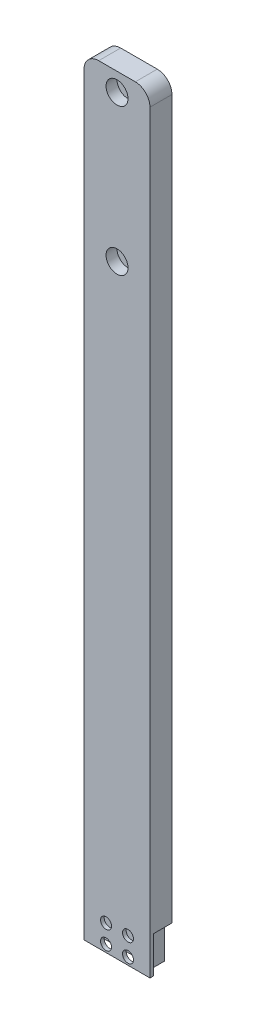
SolidWorks part; units mm, degrees
ref_plane "前视基准面" through (0, 0, 0) normal (0, 0, 1) x (1, 0, 0)
ref_plane "上视基准面" through (0, 0, 0) normal (0, 1, 0) x (1, 0, 0)
ref_plane "右视基准面" through (0, 0, 0) normal (1, 0, 0) x (0, 0, -1)
sketch "草图1" plane through (0, 0, 0) normal (0, 0, 1) x (1, 0, 0)
  line L0 (-33.0923, 146.8308) -> (-33.0923, -53.1692) construction
  line L1 (-42.0923, 146.8308) -> (-24.0923, 146.8308)
  line L2 (-42.0923, 146.8308) -> (-42.0923, -53.1692)
  line L3 (-42.0923, -53.1692) -> (-24.0923, -53.1692)
  line L4 (-24.0923, 146.8308) -> (-24.0923, -53.1692)
  circle A0 centre (-33.0923, 141.8308) radius 3
  circle A1 centre (-33.0923, 101.8308) radius 3
  dimension "D3" = 40
  dimension "D5" = 6
  dimension "D6" = 6
  dimension "D1" = 18
  dimension "D2" = 200
  dimension "D4" = 5
extrude "凸台-拉伸1" add sketch "草图1" along normal blind 6
sketch "草图2" plane through (0, -53.1692, 0) normal (0, -1, 0) x (1, 0, 0)
  line L0 (-33.0923, 0) -> (-33.0923, 6) construction
  line L6 (-40.0923, 5.4513) -> (-40.0923, 3)
  line L8 (-26.0923, 5.4513) -> (-26.0923, 3)
  line L9 (-40.0923, 5.4513) -> (-33.0923, 3) construction
  line L10 (-33.0923, 3) -> (-26.0923, 5.4513) construction
  line L11 (-24.0923, 0) -> (-42.0923, 0) construction
  line L12 (-24.0923, 6) -> (-42.0923, 6) construction
  line L13 (-42.0923, 3) -> (-33.0923, 3) construction
  line L14 (-42.0923, 6) -> (-42.0923, 0) construction
  line L15 (-24.0923, 6) -> (-24.0923, 0) construction
  line L19 (-26.0923, 5.4513) -> (-26.0923, 4.5513)
  line L21 (-40.0923, 5.4513) -> (-40.0923, 4.5513)
  line L22 (-26.0923, 5.4513) -> (-40.0923, 4.5513) construction
  line L23 (-26.0923, 4.5513) -> (-40.0923, 5.4513) construction
  line L24 (-24.0923, 0) -> (-42.0923, 0) construction
  line L25 (-26.0923, 3) -> (-40.0923, 3)
  line L27 (-26.0923, 4.5513) -> (-26.0923, 0)
  line L28 (-26.0923, 0) -> (-40.0923, 0)
  line L29 (-40.0923, 4.5513) -> (-40.0923, 0)
  line L30 (-26.0923, 4.5513) -> (-40.0923, 0) construction
  line L31 (-26.0923, 0) -> (-40.0923, 4.5513) construction
  point P4 (-33.0923, 3)
  point P18 (-33.0923, 3)
  point P19 (-33.0923, 3)
  point P23 (-33.0923, 5.0013)
  point P26 (-33.0923, 2.2757)
  line M2 (-42.0923, 0) -> (-24.0923, 0)
  dimension "D1" = 14
  dimension "D2" = 3
  dimension "D3" = 2
  dimension "D4" = 0.9
extrude "凸台-拉伸2" add sketch "草图2" along normal blind 10 contours L25 L29 L27 M2
sketch "草图3" plane through (0, 0, 6) normal (0, 0, 1) x (1, 0, 0)
  line L0 (-42.0923, -53.1692) -> (-24.0923, -53.1692) construction
  line L1 (-38.0923, -54.8692) -> (-35.5715, -54.8692) construction
  line L2 (-35.5715, -54.8692) -> (-33.0715, -54.8692) construction
  line L3 (-33.0715, -54.8692) -> (-30.0715, -54.8692) construction
  circle A0 centre (-38.0923, -54.8692) radius 1
  circle A1 centre (-35.5715, -54.8692) radius 1
  circle A2 centre (-33.0715, -54.8692) radius 1
  circle A3 centre (-30.0715, -54.8692) radius 1
  dimension "D1" = 1.7
sketch "草图4" plane through (0, 0, 6) normal (0, 0, 1) x (1, 0, 0)
  line L0 (-42.0923, -53.1692) -> (-24.0923, -53.1692) construction
  line L1 (-42.0923, -53.1692) -> (-24.0923, -53.1692)
  line L2 (-42.0923, -53.1692) -> (-42.0923, -57.1692)
  line L3 (-42.0923, -57.1692) -> (-24.0923, -57.1692)
  line L4 (-24.0923, -53.1692) -> (-24.0923, -57.1692)
  line L5 (-42.0923, -53.1692) -> (-24.0923, -57.1692) construction
  line L6 (-42.0923, -57.1692) -> (-24.0923, -53.1692) construction
  point P4 (-33.0923, -55.1692)
  dimension "D1" = 18
  dimension "D2" = 4
sketch "草图5" plane through (0, 0, 6) normal (0, 0, 1) x (1, 0, 0)
  line L1 (-42.0923, -53.1692) -> (-24.0923, -53.1692)
  line L2 (-42.0923, -53.1692) -> (-42.0923, -63.1692)
  line L3 (-42.0923, -63.1692) -> (-24.0923, -63.1692)
  line L4 (-24.0923, -53.1692) -> (-24.0923, -63.1692)
  line L5 (-42.0923, -53.1692) -> (-24.0923, -63.1692) construction
  line L6 (-42.0923, -63.1692) -> (-24.0923, -53.1692) construction
  point P4 (-33.0923, -58.1692)
  dimension "D1" = 18
  dimension "D2" = 10
extrude "凸台-拉伸4" add sketch "草图5" against normal blind 1
sketch "草图7" plane through (0, 0, 5) normal (0, 0, -1) x (-1, 0, 0)
  line L0 (40.0923, -63.1692) -> (40.0923, -53.1692) construction
  line L1 (42.0923, -63.1692) -> (24.0923, -63.1692) construction
  line L2 (24.0923, -53.1692) -> (26.0923, -53.1692) construction
  line L4 (40.0923, -53.1692) -> (42.0923, -53.1692) construction
  circle A0 centre (30.0923, -56.1692) radius 1.5
  circle A3 centre (36.0923, -56.1692) radius 1.5
  circle A5 centre (30.0923, -61.1692) radius 1.5
  circle A7 centre (36.0923, -61.1692) radius 1.5
  point P18 (41.0923, -53.1692)
  dimension "D5" = 3
  dimension "D2" = 7
  dimension "D3" = 7
  dimension "D6" = 4
  dimension "D7" = 3
  dimension "D8" = 6
  dimension "D9" = 5
  dimension "D11" = 3
  dimension "D12" = 3
  dimension "D4" = 4
  dimension "D13" = 3
  dimension "D14" = 5
extrude "切除-拉伸2" cut sketch "草图7" along normal through all and the other way blind 3
sketch "草图8" plane through (0, 0, 0) normal (0, 0, -1) x (-1, 0, 0)
  circle A0 centre (33.0923, 141.8308) radius 3
  circle A1 centre (33.0923, 101.8308) radius 3
extrude "凸台-拉伸5" add sketch "草图8" against normal blind 3
fillet "圆角1" radius 4 2 edges at (-24.0923, 146.8308, 3) (-42.0923, 146.8308, 3)
